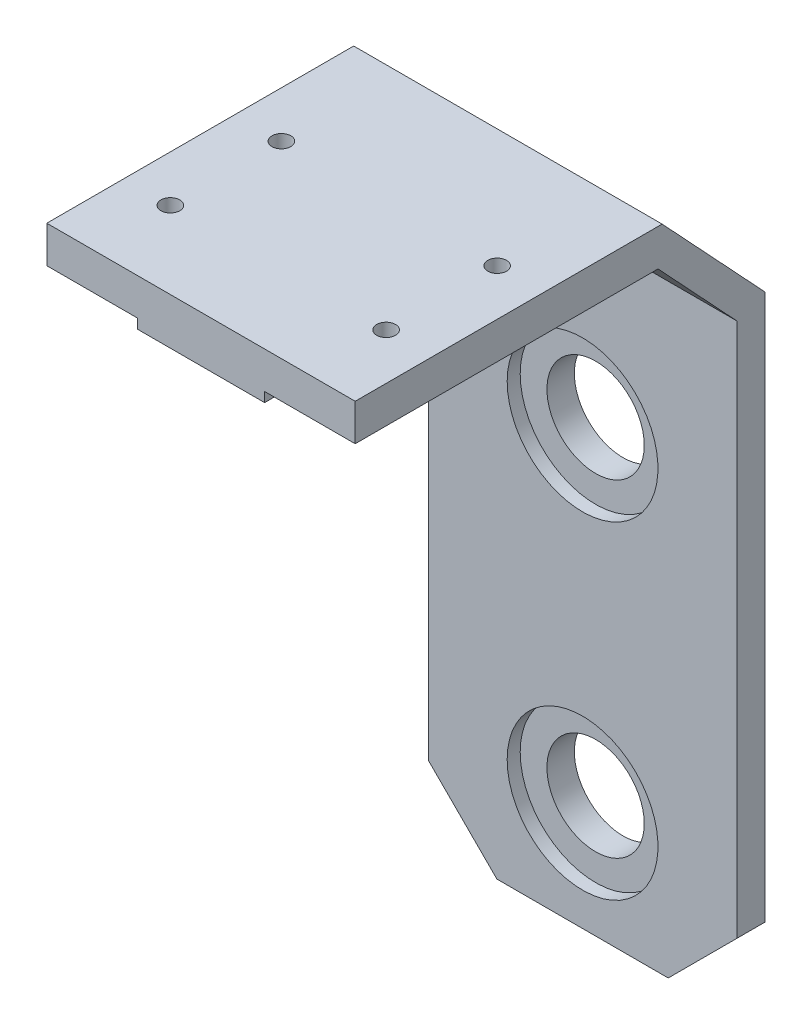
SolidWorks part; units mm, degrees
material "PLA"
ref_plane "Front Plane" through (0, 0, 0) normal (0, 0, 1) x (1, 0, 0)
ref_plane "Top Plane" through (0, 0, 0) normal (0, 1, 0) x (1, 0, 0)
ref_plane "Right Plane" through (0, 0, 0) normal (1, 0, 0) x (0, 0, -1)
sketch "Sketch1" plane through (0, 0, 0) normal (0, 0, 1) x (1, 0, 0)
  line L0 (0, -28.15) -> (0, 19.65) construction
  line L1 (-22.5, -44) -> (22.5, -44)
  line L2 (-22.5, -44) -> (-22.5, 42)
  line L3 (-22.5, 42) -> (22.5, 42)
  line L4 (22.5, -44) -> (22.5, 42)
  line L5 (0, 19.65) -> (22.5, 19.65) construction
  circle A0 centre (0, 19.65) radius 7.1
  circle A1 centre (0, -28.15) radius 7.1
  point P8 (0, 42)
  dimension "D3" = 14.2
  dimension "D4" = 14.2
  dimension "D1" = 45
  dimension "D2" = 86
  dimension "D5" = 47.8
extrude "Boss-Extrude1" add sketch "Sketch1" along normal blind 4
sketch "Sketch2" plane through (22.5, 0, 0) normal (1, 0, 0) x (0, 0, -1)
  line L0 (-4, 42) -> (-17.386, 56.3434)
  line L1 (-18.3995, 61.7155) -> (0, 42)
  line L2 (-4, 42) -> (0, 42)
  spline S0 degree 3 poles (-2014.4324, -19.1061) (19.3209, 136.6863) (-24.8796, 92.8702) (-17.0596, 54.6043) (-17.0529, 54.5296) (-17.0533, 53.872) (-17.0538, 47.5105) (-17.0544, 40.908) (-17.0552, 34.8675) (-17.0525, 34.563) (-17.0625, 34.3936) (-28.231, -39.593) (-1.5149, -116.9494) (-2012.287, -34.5153) knots -0.881536 -0.881536 -0.881536 -0.881536 0.129883 0.131348 0.131456 0.131836 0.148438 0.296875 0.304199 0.304688 0.304742 0.308594 2.23779 2.23779 2.23779 2.23779 only from (-17.0859, 54.7337) to (-17.6041, 30.65) construction
  spline S1 degree 3 poles (-18.3995, 61.7155) (-17.9641, 59.933) (-17.6988, 58.1353) (-17.386, 56.3434) knots 0.068293 0.068293 0.068293 0.068293 0.115576 0.115576 0.115576 0.115576
extrude "Boss-Extrude2" add sketch "Sketch2" against normal up to surface (45 mm away) up to face at (-22.5, -1, 2)
ref_plane "Plane1" through (0, 0, 18.28) normal (0, 0, 1) x (1, 0, 0)
sketch "Sketch3" plane through (0, 0, 18.28) normal (0, 0, 1) x (1, 0, 0)
  line L2 (-22.5, 56.3434) -> (22.5, 56.3434)
  line L3 (22.5, 61.7155) -> (-22.5, 61.7155)
  line L4 (-22.5, 56.3434) -> (22.5, 56.3434)
  line L5 (22.5, 61.7155) -> (-22.5, 61.7155)
  line L8 (-22.5, 61.7155) -> (-22.5, 56.3434)
  line L9 (-22.5, 61.7155) -> (-22.5, 56.3434)
  line L10 (22.5, 56.3434) -> (22.5, 61.7155)
  line L11 (22.5, 56.3434) -> (22.5, 61.7155)
  dimension "D1" = 0
extrude "Boss-Extrude3" add sketch "Sketch3" along normal blind 40 and the other way up to surface other way up to face at (0, 59.0295, 17.8927)
sketch "Sketch4" plane through (0, 0, 58.28) normal (0, 0, 1) x (1, 0, 0)
  line L2 (-22.5, 56.3434) -> (22.5, 56.3434)
  line L3 (22.5, 61.7155) -> (-22.5, 61.7155)
  line L4 (-22.5, 56.3434) -> (22.5, 56.3434)
  line L5 (22.5, 61.7155) -> (-22.5, 61.7155)
  spline S2 degree 1 poles (-22.5, 3061.698) (-22.5, -2943.6427) knots -558.436423 -558.436423 559.437101 559.437101 only from (-22.5, 61.7155) to (-22.5, 56.3434)
  spline S3 degree 1 poles (22.5, -2943.6391) (22.5, 3061.7016) knots -558.436423 -558.436423 559.437101 559.437101 only from (22.5, 56.3434) to (22.5, 61.7155)
  spline S4 degree 1 poles (-22.5, 61.7155) (-22.5, 56.3434) knots 0 0 1 1
  spline S5 degree 1 poles (22.5, 56.3434) (22.5, 61.7155) knots 0 0 1 1
  dimension "D1" = 0
extrude "Boss-Extrude4" add sketch "Sketch4" along normal up to surface (3.295 mm away)
sketch "Sketch5" plane through (0, 0, 61.575) normal (0, 0, 1) x (1, 0, 0)
  line L0 (22.5, 56.3434) -> (-22.5, 56.3434) construction
  line L2 (-9.493, 56.2434) -> (-9.493, 56.3434) construction
  line L3 (-9.493, 56.3434) -> (9.4868, 56.3434) construction
  line L4 (9.4868, 56.2434) -> (9.4868, 56.3434) construction
  line L6 (-9.293, 56.3434) -> (9.2868, 56.3434)
  line L7 (-9.293, 56.3434) -> (-9.293, 54.9337)
  line L8 (-9.293, 54.9337) -> (9.2868, 54.9337)
  line L9 (9.2868, 56.3434) -> (9.2868, 54.9337)
  dimension "D1" = 0.2
  dimension "D2" = 0.2
extrude "Boss-Extrude5" add sketch "Sketch5" against normal up to vertex (44.189 mm away)
chamfer "Chamfer2" distance 1.405 angle 45 1 edges at (-0.0031, 54.9337, 17.386)
sketch "Sketch7" plane through (22.5, 0, 0) normal (1, 0, 0) x (0, 0, -1)
  line L0 (-18.28, 61.7155) -> (-16.7937, 61.7155)
  line L1 (-16.7937, 61.7155) -> (0, 43.7206)
  line L2 (0, 42) -> (-18.28, 61.5875) construction
  line L3 (0, 42) -> (0, 43.7206)
  line L4 (-18.28, 61.7155) -> (-18.28, 61.5875)
  line L5 (-18.28, 61.5875) -> (0, 42)
extrude "Boss-Extrude7" add sketch "Sketch7" against normal up to surface (45 mm away) up to face at (-22.5, 32.6339, 20.5662)
sketch "Sketch8" plane through (0, 61.7155, 0) normal (0, 1, 0) x (1, 0, 0)
  circle A0 centre (15.735, -50.299) radius 1.375 construction
  circle A1 centre (15.735, -34.0971) radius 1.375 construction
  circle A2 centre (-15.743, -34.0971) radius 1.375 construction
  circle A3 centre (-15.743, -50.299) radius 1.375 construction
  circle A4 centre (15.735, -50.299) radius 1.375
  circle A5 centre (15.735, -34.0971) radius 1.375
  circle A6 centre (-15.743, -34.0971) radius 1.375
  circle A7 centre (-15.743, -50.299) radius 1.375
extrude "Cut-Extrude1" cut sketch "Sketch8" against normal through all
chamfer "Chamfer3" distance 10 angle 45 2 edges at (22.5, -44, 2) (-22.5, -44, 2)
chamfer "Chamfer4" distance 1.75 angle 45 5 edges at (-22.5, 4.8603, 0) (-17.5, -39, 0) (0, -44, 0) (17.5, -39, 0) (22.5, 4.8603, 0)
sketch "Sketch9" plane through (0, 0, 4) normal (0, 0, 1) x (1, 0, 0)
  line L1 (-22.5, 46.4753) -> (22.5, 46.4753)
  line L2 (-22.5, 46.4753) -> (-22.5, -34)
  line L6 (12.5, -44) -> (22.5, -34) construction
  line L7 (-12.5, -44) -> (12.5, -44) construction
  line L8 (-22.5, -34) -> (-12.5, -44) construction
  line L9 (12.5, -44) -> (22.5, -34)
  line L10 (-12.5, -44) -> (12.5, -44)
  line L11 (-22.5, -34) -> (-12.5, -44)
  line L12 (22.5, 46.4753) -> (22.5, -34)
  circle A0 centre (0, 19.65) radius 11
  circle A1 centre (0, -28.15) radius 11
  line M9 (-12.5, -44) -> (12.5, -44)
  line M10 (12.5, -44) -> (22.5, -34)
  line M11 (22.5, -34) -> (22.5, 42)
  line M12 (22.5, 42) -> (-22.5, 42)
  line M13 (-22.5, 42) -> (-22.5, -34)
  line M14 (-22.5, -34) -> (-12.5, -44)
  dimension "D2" = 22
  dimension "D3" = 22
extrude "Boss-Extrude8" add sketch "Sketch9" along normal blind 1.9 contours A1 A0 M14 M9 M10 M11 M12 M13 | L12 L1 L2 M12
